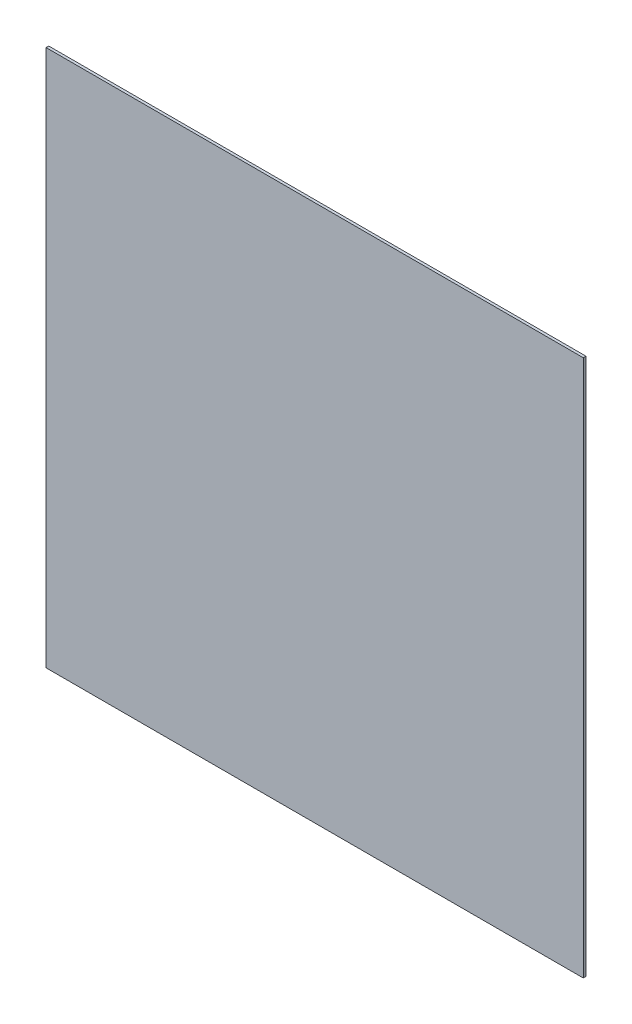
SolidWorks part; units mm, degrees
ref_plane "Front Plane" through (0, 0, 0) normal (0, 0, 1) x (1, 0, 0)
ref_plane "Top Plane" through (0, 0, 0) normal (0, 1, 0) x (1, 0, 0)
ref_plane "Right Plane" through (0, 0, 0) normal (1, 0, 0) x (0, 0, -1)
sketch "Sketch1" plane through (0, 0, 0) normal (0, 0, 1) x (1, 0, 0)
  line L1 (-696.1451, 94.6712) -> (303.8549, 94.6712)
  line L2 (-696.1451, 94.6712) -> (-696.1451, -905.3288)
  line L3 (-696.1451, -905.3288) -> (303.8549, -905.3288)
  line L4 (303.8549, 94.6712) -> (303.8549, -905.3288)
  dimension "D1" = 1000
  dimension "D2" = 1000
extrude "Boss-Extrude1" add sketch "Sketch1" along normal blind 5 contours L2 L3 L4 L1
